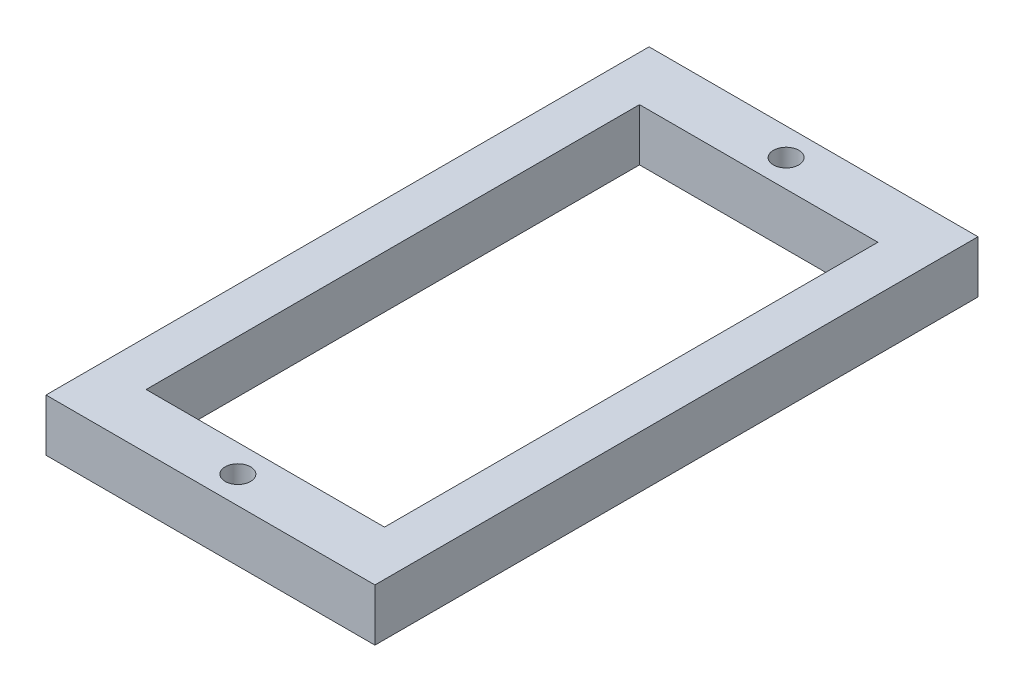
SolidWorks part; units mm, degrees
ref_plane "Front Plane" through (0, 0, 0) normal (0, 0, 1) x (1, 0, 0)
ref_plane "Top Plane" through (0, 0, 0) normal (0, 1, 0) x (1, 0, 0)
ref_plane "Right Plane" through (0, 0, 0) normal (1, 0, 0) x (0, 0, -1)
sketch "Sketch2" plane through (0, 0, 0) normal (0, 1, 0) x (1, 0, 0)
  line L0 (-7.1732, 45.1748) -> (-7.1732, -24.6752) construction
  line L1 (-26.2232, 45.1748) -> (11.8768, 45.1748)
  line L2 (-26.2232, 45.1748) -> (-26.2232, -24.6752)
  line L3 (-26.2232, -24.6752) -> (11.8768, -24.6752)
  line L4 (11.8768, 45.1748) -> (11.8768, -24.6752)
  line L5 (-26.2232, 10.2498) -> (11.8768, 10.2498) construction
  line L7 (-20.9781, 38.8248) -> (6.6317, 38.8248)
  line L8 (-20.9781, 38.8248) -> (-20.9781, -18.3252)
  line L9 (-20.9781, -18.3252) -> (6.6317, -18.3252)
  line L10 (6.6317, 38.8248) -> (6.6317, -18.3252)
  line L11 (-20.9781, 38.8248) -> (6.6317, -18.3252) construction
  line L12 (-20.9781, -18.3252) -> (6.6317, 38.8248) construction
  circle A0 centre (-7.1732, 41.9998) radius 1.4732
  circle A2 centre (-7.1732, -21.5002) radius 1.4732
  point P0 (-7.1732, 10.2498)
  dimension "D3" = 27.6098
  dimension "D6" = 38.1
  dimension "D4" = 3.175
  dimension "D1" = 69.85
  dimension "D2" = 57.15
extrude "Boss-Extrude1" add sketch "Sketch2" along normal blind 6.0452
